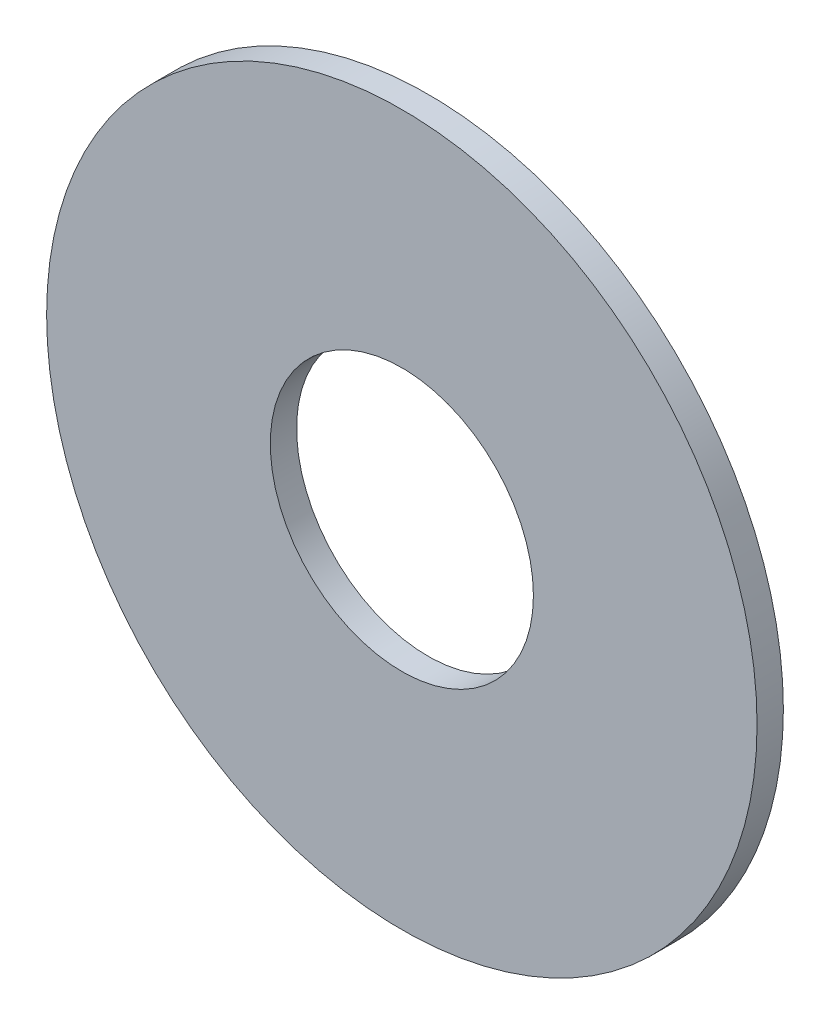
SolidWorks part; units mm, degrees
material "PMMA"
ref_plane "Front Plane" through (0, 0, 0) normal (0, 0, 1) x (1, 0, 0)
ref_plane "Top Plane" through (0, 0, 0) normal (0, 1, 0) x (1, 0, 0)
ref_plane "Right Plane" through (0, 0, 0) normal (1, 0, 0) x (0, 0, -1)
sketch "草图1" plane through (0, 0, 0) normal (0, 0, 1) x (1, 0, 0)
  circle A0 centre (0, 0) radius 27
  circle A1 centre (0, 0) radius 10
extrude "凸台-拉伸1" add sketch "草图1" along normal blind 2
